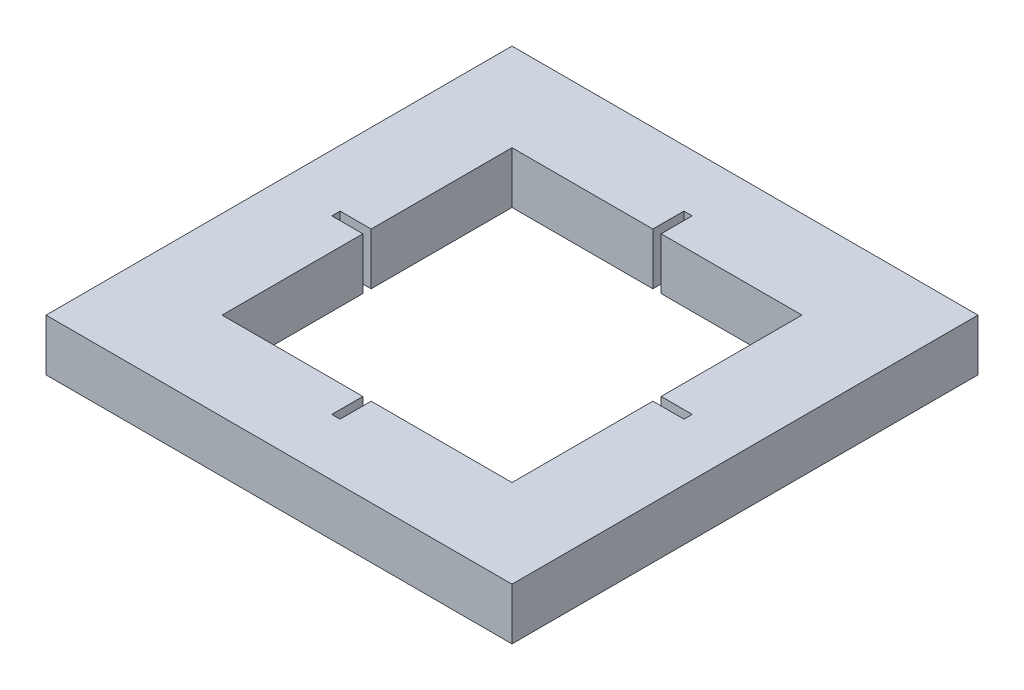
SolidWorks part; units mm, degrees
ref_plane "Alzado" through (0, 0, 0) normal (0, 0, 1) x (1, 0, 0)
ref_plane "Planta" through (0, 0, 0) normal (0, 1, 0) x (1, 0, 0)
ref_plane "Vista lateral" through (0, 0, 0) normal (1, 0, 0) x (0, 0, -1)
sketch "Croquis1" plane through (0, 0, 0) normal (0, 1, 0) x (1, 0, 0)
  line L0 (0, 0) -> (45, -45) construction
  line L1 (0, 0) -> (45, 0)
  line L2 (0, 0) -> (0, -45)
  line L3 (0, -45) -> (45, -45)
  line L4 (45, 0) -> (45, -45)
  line L6 (8.5, -8.5) -> (36.5, -8.5)
  line L7 (8.5, -8.5) -> (8.5, -36.5)
  line L8 (8.5, -36.5) -> (36.5, -36.5)
  line L9 (36.5, -8.5) -> (36.5, -36.5)
  line L10 (8.5, -8.5) -> (36.5, -36.5) construction
  line L11 (8.5, -36.5) -> (36.5, -8.5) construction
  point P4 (22.5, -22.5)
  dimension "D1" = 45
  dimension "D2" = 28
extrude "Saliente-Extruir1" add sketch "Croquis1" along normal blind 5
sketch "Croquis2" plane through (0, 0, 0) normal (0, -1, 0) x (1, 0, 0)
  line L0 (8.5, 36.5) -> (36.5, 36.5) construction
  line L1 (22.1, 36.5) -> (22.9, 36.5)
  line L2 (22.1, 36.5) -> (22.1, 39.5)
  line L3 (22.1, 39.5) -> (22.9, 39.5)
  line L4 (22.9, 36.5) -> (22.9, 39.5)
  line L5 (22.5, 39.5) -> (22.5, 45) construction
  line L6 (0, 45) -> (45, 45) construction
  line L7 (0, 22.5) -> (45, 22.5) construction
  line L8 (0, 0) -> (0, 45) construction
  line L9 (45, 45) -> (45, 0) construction
  line L10 (22.5, 0) -> (22.5, 45) construction
  line L11 (45, 0) -> (0, 0) construction
  line L12 (36.5, 36.5) -> (36.5, 8.5) construction
  line L13 (36.5, 22.1) -> (39.5, 22.1)
  line L14 (36.5, 22.1) -> (36.5, 22.9)
  line L15 (36.5, 22.9) -> (39.5, 22.9)
  line L16 (39.5, 22.1) -> (39.5, 22.9)
  line L17 (22.1, 5.5) -> (22.9, 5.5)
  line L18 (22.9, 8.5) -> (22.9, 5.5)
  line L19 (22.1, 8.5) -> (22.9, 8.5)
  line L20 (22.1, 8.5) -> (22.1, 5.5)
  line L21 (8.5, 22.9) -> (5.5, 22.9)
  line L22 (5.5, 22.1) -> (5.5, 22.9)
  line L23 (8.5, 22.1) -> (5.5, 22.1)
  line L24 (8.5, 22.1) -> (8.5, 22.9)
  point P25 (39.5, 22.5)
  dimension "D1" = 0.8
  dimension "D2" = 3
  dimension "D3" = 3
  dimension "D4" = 0.8
extrude "Cortar-Extruir1" cut sketch "Croquis2" against normal blind 5
